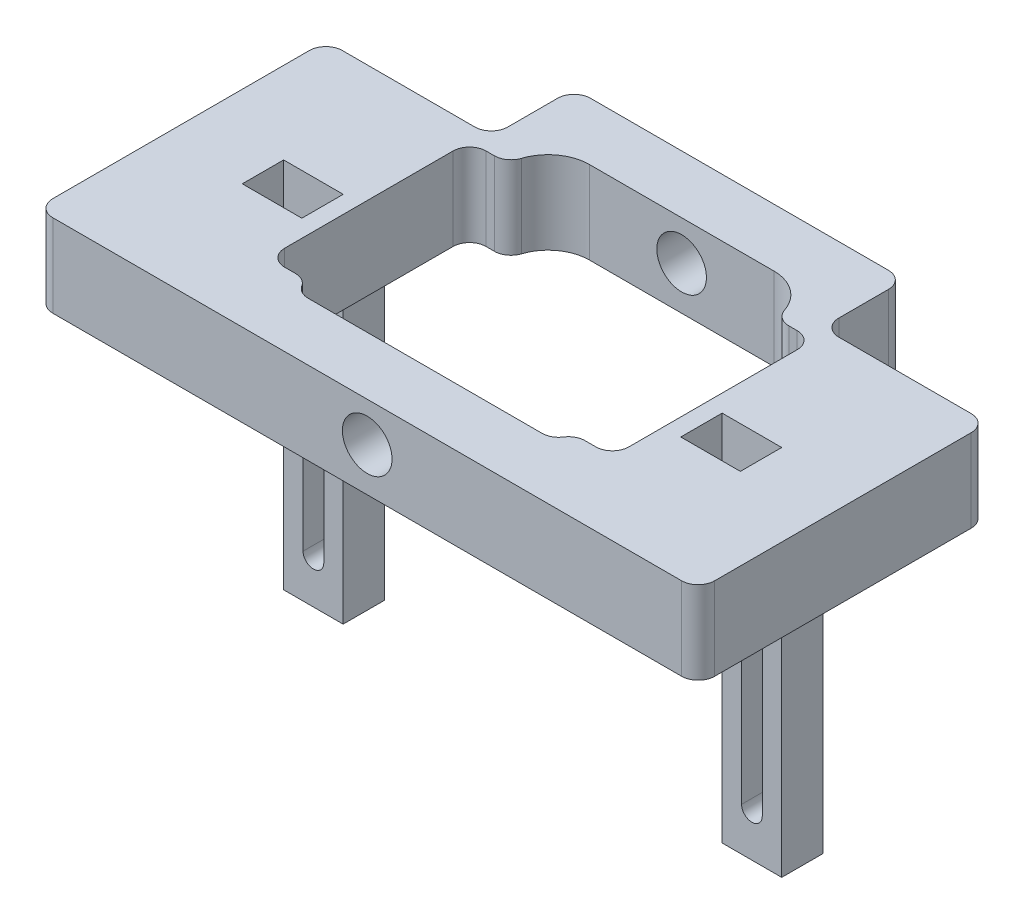
SolidWorks part; units mm, degrees
ref_plane "Front Plane" through (0, 0, 0) normal (0, 0, 1) x (1, 0, 0)
ref_plane "Top Plane" through (0, 0, 0) normal (0, 1, 0) x (1, 0, 0)
ref_plane "Right Plane" through (0, 0, 0) normal (1, 0, 0) x (0, 0, -1)
sketch "草图1" plane through (0, 0, 0) normal (0, 1, 0) x (1, 0, 0)
  line L1 (-18.4722, 10) -> (61.5278, 10)
  line L2 (-18.4722, 10) -> (-18.4722, -25)
  line L3 (-18.4722, -25) -> (61.5278, -25)
  line L4 (61.5278, 10) -> (61.5278, -25)
  line L5 (-18.4722, 10) -> (61.5278, -25) construction
  line L6 (-18.4722, -25) -> (61.5278, 10) construction
  point P0 (21.5278, -7.5)
  dimension "D1" = 35
  dimension "D2" = 80
extrude "凸台-拉伸1" add sketch "草图1" along normal blind 10
ref_plane "基准面1" through (21.5278, 0, 0) normal (-1, 0, 0) x (0, 0, 1)
ref_plane "基准面2" through (0, 0, 7.5) normal (0, 0, 1) x (1, 0, 0)
sketch "草图2" plane through (0, 10, 0) normal (0, 1, 0) x (1, 0, 0)
  line L1 (-8.5722, -5.0005) -> (-1.3722, -5.0005)
  line L2 (-8.5722, -5.0005) -> (-8.5722, -10.0005)
  line L3 (-8.5722, -10.0005) -> (-1.3722, -10.0005)
  line L4 (-1.3722, -5.0005) -> (-1.3722, -10.0005)
  line L5 (-8.5722, -5.0005) -> (-1.3722, -10.0005) construction
  line L6 (-8.5722, -10.0005) -> (-1.3722, -5.0005) construction
  line L7 (51.6278, -4.9985) -> (44.4278, -4.9985)
  line L8 (51.6278, -4.9985) -> (51.6278, -10.0005)
  line L9 (51.6278, -10.0005) -> (44.4278, -10.0005)
  line L10 (44.4278, -4.9985) -> (44.4278, -10.0005)
  line L11 (51.6278, -4.9985) -> (44.4278, -10.0005) construction
  line L12 (51.6278, -10.0005) -> (44.4278, -4.9985) construction
  point P0 (-4.9722, -7.5005)
  point P6 (48.0278, -7.4995)
  dimension "D1" = 7.2
  dimension "D2" = 7.2
extrude "切除-拉伸1" cut sketch "草图2" against normal blind 20
sketch "草图3" plane through (0, 0, 0) normal (0, -1, 0) x (1, 0, 0)
  line L0 (-1.3822, 4.9995) -> (-1.3822, -0.0005) construction
  line L1 (-8.5622, 5.0005) -> (-1.3822, 5.0005)
  line L2 (-8.5622, 5.0005) -> (-8.5622, 2.0005)
  line L3 (-8.5622, 2.0005) -> (-1.3822, 2.0005)
  line L4 (-1.3822, 5.0005) -> (-1.3822, 2.0005)
  line L5 (-8.4722, 2.0005) -> (-1.4722, 2.0005) construction
  line L6 (21.5278, -21.9995) -> (21.5278, 30.7654) construction
  line L7 (44.4378, 5.0005) -> (44.4378, 2.0005)
  line L8 (51.6178, 2.0005) -> (44.4378, 2.0005)
  line L9 (51.6178, 5.0005) -> (51.6178, 2.0005)
  line L10 (51.6178, 5.0005) -> (44.4378, 5.0005)
sketch "草图6" plane through (0, 10, 0) normal (0, 1, 0) x (1, 0, 0)
  line L0 (21.5278, 10) -> (21.5278, -3.0005) construction
  line L1 (-8.5722, -5.0005) -> (-1.3822, -5.0005)
  line L2 (-8.5722, -5.0005) -> (-8.5722, -0.0005)
  line L3 (-8.5722, -0.0005) -> (-1.3822, -0.0005)
  line L4 (-1.3822, -5.0005) -> (-1.3822, -0.0005)
  line L5 (61.5278, 10) -> (-18.4722, 10) construction
  line L6 (44.4378, -5.0005) -> (44.4378, -0.0005)
  line L7 (51.6278, -0.0005) -> (44.4378, -0.0005)
  line L8 (51.6278, -5.0005) -> (51.6278, -0.0005)
  line L9 (51.6278, -5.0005) -> (44.4378, -5.0005)
  dimension "D1" = 5
extrude "凸台-拉伸7" add sketch "草图6" against normal blind 45
sketch "草图7" plane through (0, 0, 5.0005) normal (0, 0, 1) x (1, 0, 0)
  circle A0 centre (-4.9722, -12) radius 1.25
  circle A1 centre (48.0278, -12) radius 1.25
extrude "切除-拉伸2" cut sketch "草图7" against normal blind 30
sketch "草图8" plane through (0, 0, -10) normal (0, 0, -1) x (-1, 0, 0)
  line L0 (-61.5278, 10) -> (18.4722, 10) construction
  line L1 (-41.5278, 10) -> (-1.5278, 10)
  line L2 (-41.5278, 10) -> (-41.5278, 0)
  line L3 (-41.5278, 0) -> (-1.5278, 0)
  line L4 (-1.5278, 10) -> (-1.5278, 0)
  line L5 (-61.5278, 0) -> (18.4722, 0) construction
  line L6 (18.4722, 10) -> (18.4722, 0) construction
  line L7 (-61.5278, 10) -> (-61.5278, 0) construction
  dimension "D1" = 20
  dimension "D2" = 20
extrude "凸台-拉伸8" add sketch "草图8" along normal blind 10
sketch "草图9" plane through (0, 10, 0) normal (0, 1, 0) x (1, 0, 0)
  line L0 (21.5278, 20) -> (21.5278, -25) construction
  line L1 (1.5278, 20) -> (41.5278, 20) construction
  line L2 (-18.4722, -25) -> (61.5278, -25) construction
  line L8 (30.3425, -25.2811) -> (12.713, 20.2811) construction
  line L9 (30.3425, 20.2811) -> (12.713, -25.2811) construction
  circle A0 centre (14.5288, 21.9995) radius 2.5 construction
  point P6 (21.5278, -2.5)
sketch "草图10" plane through (0, 10, 0) normal (0, 1, 0) x (1, 0, 0)
  line L0 (21.5278, 20) -> (21.5278, -25) construction
  line L1 (1.5278, 20) -> (41.5278, 20) construction
  line L2 (-18.4722, -25) -> (61.5278, -25) construction
  line L3 (-8.4722, -18.0005) -> (51.5278, -18.0005) construction
  line L4 (5.3907, 13.0005) -> (37.6649, 13.0005)
  line L5 (5.3907, 13.0005) -> (5.3907, -18.0005)
  line L6 (5.3907, -18.0005) -> (37.6649, -18.0005)
  line L7 (37.6649, 13.0005) -> (37.6649, -18.0005)
  line L8 (5.3907, 13.0005) -> (37.6649, -18.0005) construction
  line L9 (5.3907, -18.0005) -> (37.6649, 13.0005) construction
  point P6 (21.5278, -2.5)
extrude "切除-拉伸3" cut sketch "草图10" against normal blind 10
fillet "圆角1" radius 5 2 edges at (37.6649, 5, -13.0005) (5.3907, 5, -13.0005)
fillet "圆角2" radius 2 2 edges at (37.6649, 5, 18.0005) (5.3907, 5, 18.0005)
sketch "草图11" plane through (0, 0, 25) normal (0, 0, 1) x (1, 0, 0)
  circle A0 centre (21.5278, 5.2311) radius 3
  dimension "D1" = 6
extrude "切除-拉伸4" cut sketch "草图11" against normal blind 50
sketch "草图12" plane through (0, 0, 5.0005) normal (0, 0, 1) x (1, 0, 0)
  line L0 (-4.9722, -9.0862) -> (-4.9722, -29.7777) construction
  line L1 (-3.7222, -9.0862) -> (-3.7222, -29.7777)
  line L2 (-6.2222, -9.0862) -> (-6.2222, -29.7777)
  line L3 (21.5278, 5.341) -> (21.5278, -14.528) construction
  line L4 (21.5278, 5.5) -> (21.5278, -5.5) construction
  line L5 (48.0278, -9.0862) -> (48.0278, -29.7777) construction
  line L6 (46.7778, -9.0862) -> (46.7778, -29.7777)
  line L7 (49.2778, -9.0862) -> (49.2778, -29.7777)
  circle A0 centre (-4.9722, -27) radius 1.25 construction
  circle A1 centre (48.0278, -27) radius 1.25 construction
  arc A2 (-3.7222, -9.0862) -> (-6.2222, -9.0862) centre (-4.9722, -9.0862) ccw
  arc A3 (-6.2222, -29.7777) -> (-3.7222, -29.7777) centre (-4.9722, -29.7777) ccw
  arc A4 (46.7778, -9.0862) -> (49.2778, -9.0862) centre (48.0278, -9.0862) cw
  arc A5 (49.2778, -29.7777) -> (46.7778, -29.7777) centre (48.0278, -29.7777) cw
  point P8 (-4.9722, -19.4319)
  point P19 (48.0278, -19.4319)
  dimension "D1" = 1.25
extrude "切除-拉伸5" cut sketch "草图12" against normal blind 50
fillet "圆角3" radius 2 8 edges at (61.5278, 5, -10) (61.5278, 5, 25) (-18.4722, 5, 25) (-18.4722, 5, -10) (1.5278, 5, -20) (41.5278, 5, -20) (41.5278, 5, -10) (1.5278, 5, -10)
sketch "草图13" plane through (0, 0, 0) normal (0, -1, 0) x (1, 0, 0)
  line L1 (-8.5622, 14.3774) -> (-1.3822, 14.3774)
  line L2 (-8.5622, 14.3774) -> (-8.5622, 12.2676)
  line L3 (-8.5622, 12.2676) -> (-1.3822, 12.2676)
  line L4 (-1.3822, 14.3774) -> (-1.3822, 12.2676)
extrude "凸台-拉伸9" add sketch "草图13" along normal blind 10
fillet "圆角4" [suppressed] radius 5
sketch "草图14" plane through (0, 10, 0) normal (0, 1, 0) x (1, 0, 0)
  line L0 (37.6649, -4) -> (5.3907, -4) construction
  line L1 (37.6649, -16.0005) -> (37.6649, 8.0005) construction
  line L2 (5.3907, 8.0005) -> (5.3907, -16.0005) construction
  line L4 (42.3279, -16.1691) -> (0.7276, -16.1691)
  line L5 (42.3279, -16.1691) -> (42.3279, 8.1691)
  line L6 (42.3279, 8.1691) -> (0.7276, 8.1691)
  line L7 (0.7276, -16.1691) -> (0.7276, 8.1691)
  line L8 (42.3279, -16.1691) -> (0.7276, 8.1691) construction
  line L9 (42.3279, 8.1691) -> (0.7276, -16.1691) construction
  point P6 (21.5278, -4)
extrude "切除-拉伸6" cut sketch "草图14" against normal blind 10
fillet "圆角5" radius 2 8 edges at (5.3978, 5, 16.1691) (37.6578, 5, 16.1691) (42.3279, 5, 16.1691) (0.7276, 5, 16.1691) (37.6621, 5, -8.1691) (5.3935, 5, -8.1691) (0.7276, 5, -8.1691) (42.3279, 5, -8.1691)
